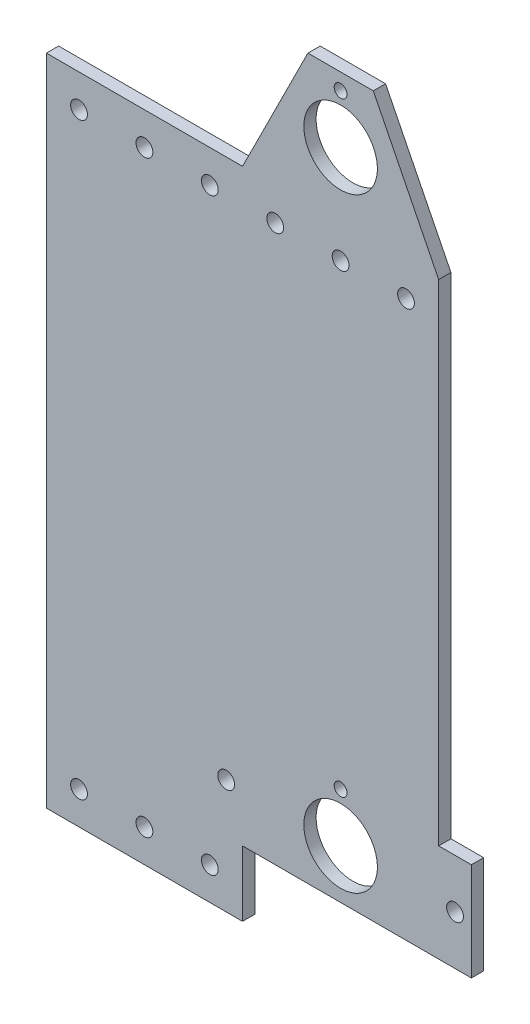
SolidWorks part; units mm, degrees
material "6061 Alloy"
ref_plane "Front Plane" through (0, 0, 0) normal (0, 0, 1) x (1, 0, 0)
ref_plane "Top Plane" through (0, 0, 0) normal (0, 1, 0) x (1, 0, 0)
ref_plane "Right Plane" through (0, 0, 0) normal (1, 0, 0) x (0, 0, -1)
sketch "Sketch1" plane through (0, 0, 0) normal (0, 0, 1) x (1, 0, 0)
  line L0 (0, 0) -> (76.2, 0) construction
  line L1 (76.2, 0) -> (76.2, 25.4)
  line L2 (76.2, 25.4) -> (50.8, 76.2)
  line L3 (50.8, 76.2) -> (25.4, 76.2)
  line L6 (-63.5, 12.7) -> (-38.1, 12.7) construction
  line L7 (76.2, 0) -> (76.2, -165.1)
  line L8 (0, 0) -> (-76.2, 0) construction
  line L9 (-76.2, 0) -> (-76.2, 25.4)
  line L11 (38.1, -203.2) -> (0, -203.2)
  line L13 (0, -203.2) -> (0, -228.6)
  line L14 (25.4, 76.2) -> (0, 25.4)
  line L15 (0, 25.4) -> (-76.2, 25.4)
  line L16 (0, -228.6) -> (-76.2, -228.6)
  line L17 (-76.2, -228.6) -> (-76.2, -215.9)
  line L18 (-76.2, -215.9) -> (-76.2, 0)
  line L19 (-12.7, -215.9) -> (-38.1, -215.9) construction
  line L21 (76.2, -165.1) -> (88.9, -165.1)
  line L22 (88.9, -165.1) -> (88.9, -203.2)
  line L23 (88.9, -203.2) -> (38.1, -203.2)
  circle A2 centre (-38.1, 12.7) radius 3.2639
  circle A3 centre (-12.7, 12.7) radius 3.2639
  circle A6 centre (-63.5, 12.7) radius 3.2639
  circle A7 centre (12.7, 12.7) radius 3.2639
  circle A8 centre (38.1, 12.7) radius 3.2639
  circle A9 centre (38.1, 50.8) radius 14.2875
  circle A16 centre (63.5, 12.7) radius 3.2639
  circle A18 centre (38.1, -184.15) radius 14.2875
  circle A22 centre (38.1, -165.1) radius 2.4892
  circle A23 centre (-12.7, -215.9) radius 3.2639
  circle A24 centre (-38.1, -215.9) radius 3.2639
  circle A25 centre (-63.5, -215.9) radius 3.2639
  circle A26 centre (38.1, 69.85) radius 2.4892
  circle A27 centre (82.55, -184.15) radius 3.2639
  circle A28 centre (-6.35, -184.15) radius 3.2639
  point P51 (5.3674, -184.15)
  dimension "D7" = 12.7
  dimension "D14" = 6.5278
  dimension "D16" = 28.575
  dimension "D18" = 25.4
  dimension "D20" = 25.4
  dimension "D21" = 12.7
  dimension "D10" = 76.2
  dimension "D13" = 203.2
  dimension "D15" = 6.5278
  dimension "D27" = 4.9784
  dimension "D30" = 4.9784
  dimension "D34" = 6.5278
  dimension "D37" = 6.5278
  dimension "D1" = 76.2
  dimension "D2" = 76.2
  dimension "D3" = 152.4
  dimension "D4" = 25.4
  dimension "D5" = 25.4
  dimension "D6" = 38.1
  dimension "D8" = 6
  dimension "D11" = 25.4
  dimension "D12" = 234.95
  dimension "D17" = 50.8
  dimension "D19" = 25.4
  dimension "D23" = 12.7
  dimension "D9" = 25.4
  dimension "D25" = 12.7
  dimension "D26" = 76.2
  dimension "D22" = 12.7
  dimension "D24" = 76.2
  dimension "D28" = 19.05
  dimension "D29" = 19.05
  dimension "D31" = 38.1
  dimension "D32" = 50.8
  dimension "D33" = 12.7
  dimension "D35" = 19.05
  dimension "D36" = 6.35
  dimension "D38" = 44.45
extrude "Boss-Extrude1" add sketch "Sketch1" along normal blind 4.7625
